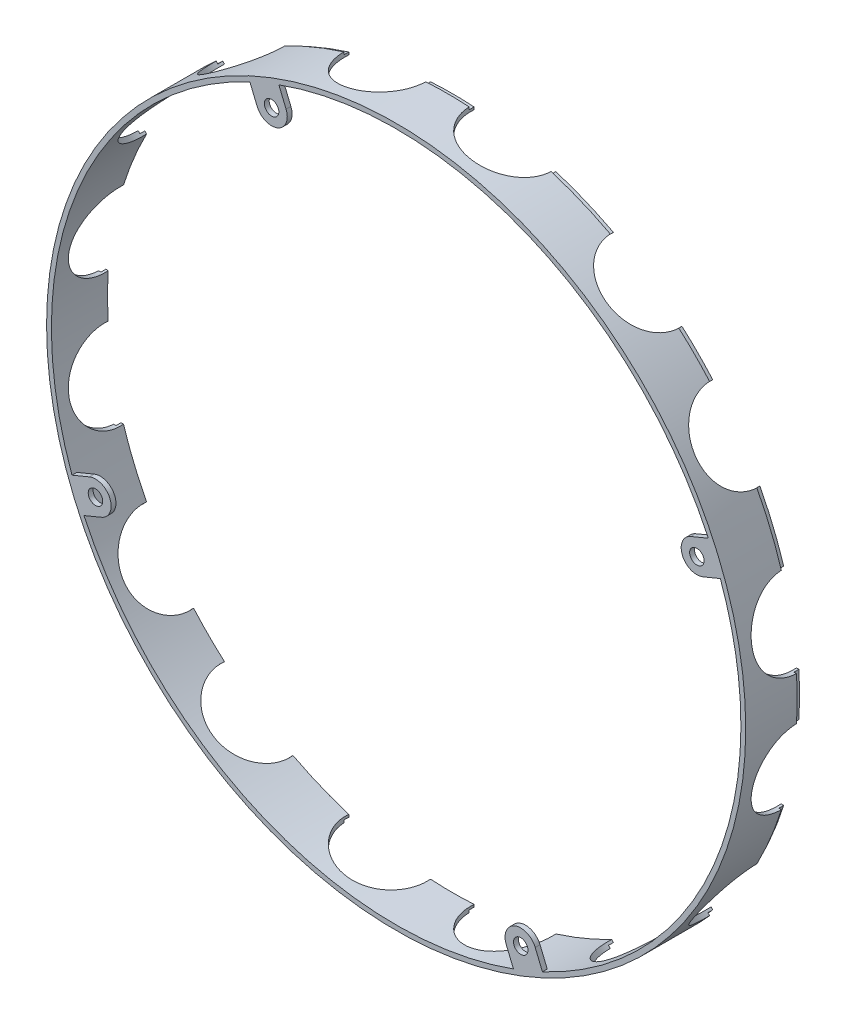
SolidWorks part; units mm, degrees
material "ABS"
ref_plane "Ebene vorne" through (0, 0, 0) normal (0, 0, 1) x (1, 0, 0)
ref_plane "Ebene oben" through (0, 0, 0) normal (0, 1, 0) x (1, 0, 0)
ref_plane "Ebene rechts" through (0, 0, 0) normal (1, 0, 0) x (0, 0, -1)
sketch "Skizze4" plane through (0, 0, 0) normal (0, 0, 1) x (1, 0, 0)
  circle A0 centre (0, 0) radius 72.5
  circle A1 centre (0, 0) radius 72
  dimension "D1" = 145
  dimension "D2" = 0.5
extrude "Base Ring" add sketch "Skizze4" against normal blind 9.65
sketch "Skizze6" plane through (0, 0, 0) normal (0, 0, 1) x (1, 0, 0)
  circle A0 centre (0, 0) radius 71.5
  circle A1 centre (0, 0) radius 72
  circle A2 centre (0, 0) radius 72 construction
  dimension "D1" = 0.5
extrude "Inner Ring" add sketch "Skizze6" against normal offset from surface (10.65 mm away) 1 up to face at (72, 0, -9.65) offset beyond the face yes
sketch "Skizze9" plane through (0, 0, 0) normal (0, 0, 1) x (1, 0, 0)
  circle A0 centre (0, 0) radius 72.5
  circle A1 centre (0, 0) radius 71.5
  circle A3 centre (0, 0) radius 72.5 construction
  circle A4 centre (0, 0) radius 71.5 construction
extrude "Upper Ring " add sketch "Skizze9" along normal blind 1
sketch "Skizze5" plane through (0, 0, 0) normal (0, 1, 0) x (1, 0, 0)
  line L0 (0, 0) -> (0, 9.65) construction
  line L1 (72.5, 9.65) -> (-72.5, 9.65) construction
  line L3 (-21.5, 9.95) -> (-4.5, 9.95)
  line L4 (-21.5, 9.95) -> (-21.5, 18.45)
  line L5 (-21.5, 18.45) -> (-4.5, 18.45)
  line L6 (-4.5, 9.95) -> (-4.5, 18.45)
  line L7 (4.5, 9.95) -> (21.5, 9.95)
  line L8 (4.5, 9.95) -> (4.5, 18.45)
  line L9 (4.5, 18.45) -> (21.5, 18.45)
  line L10 (21.5, 9.95) -> (21.5, 18.45)
  circle A0 centre (-13, 9.95) radius 8.5
  circle A1 centre (13, 9.95) radius 8.5
  dimension "D1" = 17
  dimension "D2" = 26
  dimension "D3" = 9.95
extrude "Sensor Cut" cut sketch "Skizze5" along normal through all contours A0 | A1
pattern_circular "Sensor Rotation" count 8 over 360 about axis through (0, 0, -215.2968) along (0, 0, 1) of "Sensor Cut"
sketch "Skizze8" plane through (0, 0, 0) normal (0, 0, 1) x (1, 0, 0)
  line L0 (0, 0) -> (66.9813, 27.7445) construction
  line L1 (0, 0) -> (72.5, 0) construction
  line L3 (67.2328, 24.331) -> (64.7454, 30.3362)
  line L4 (64.7454, 30.3362) -> (61.1181, 28.8337)
  line L5 (61.1181, 28.8337) -> (63.6056, 22.8285) construction
  line L6 (63.6056, 22.8285) -> (67.2328, 24.331)
  circle A1 centre (0, 0) radius 71.5
  arc A3 (61.1181, 28.8337) -> (63.6056, 22.8285) centre (62.3619, 25.8311) ccw
  circle A4 centre (62.3619, 25.8311) radius 1.5
  circle A5 centre (0, 0) radius 72.5 construction
  circle A6 centre (0, 0) radius 71.5 construction
  dimension "D2" = 67.5
  dimension "D3" = 3
  dimension "D4" = 6.5
  dimension "D1" = 22.5
extrude "Aufsatz-Linear austragen3" add sketch "Skizze8" along normal up to surface (1 mm away) contours L3 A1 | L4 A3 L6 L3 A4
pattern_circular "Kreismuster2" count 4 over 360 about axis through (0, 0, 0) along (0, 0, 1) of "Aufsatz-Linear austragen3"
equation "\"D_outer\"= 145mm"
equation "\"d_inner\"= 130mm"
equation "\"d_spacers\"= 135mm"
equation "\"d_spacer_hole\"= 3.5mm"
equation "\"D1@Skizze4\"=\"D_outer\""
